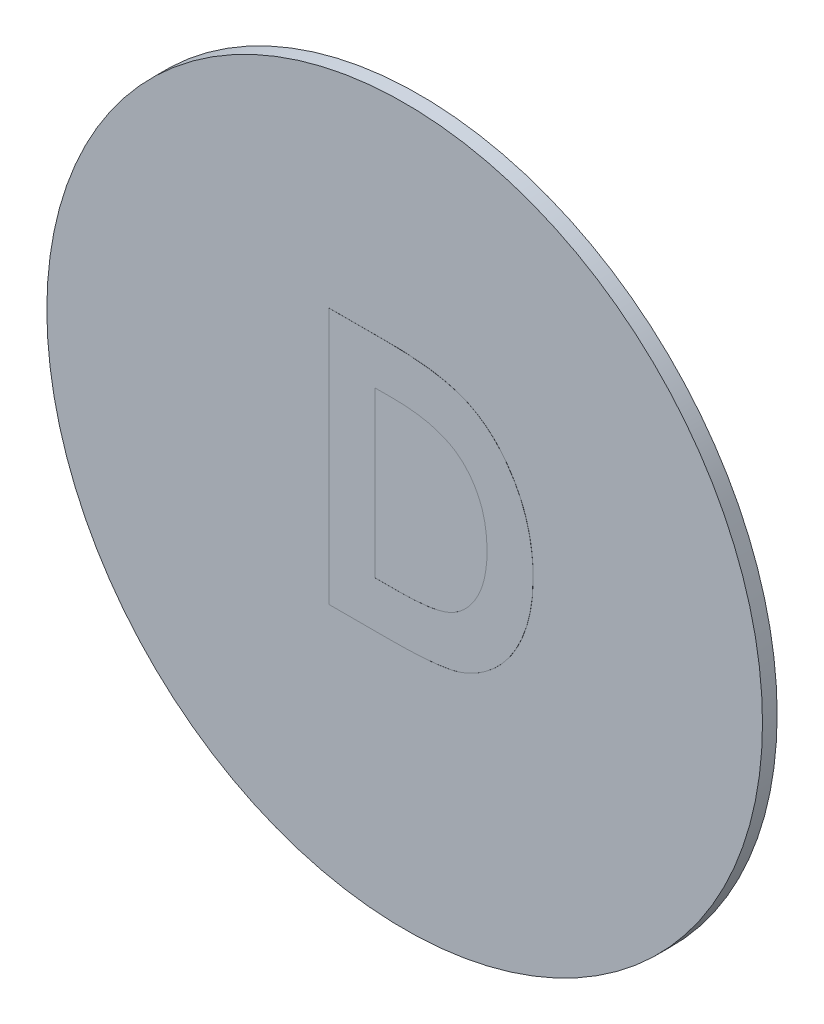
SolidWorks part; units mm, degrees
ref_plane "Front Plane" through (0, 0, 0) normal (0, 0, 1) x (1, 0, 0)
ref_plane "Top Plane" through (0, 0, 0) normal (0, 1, 0) x (1, 0, 0)
ref_plane "Right Plane" through (0, 0, 0) normal (1, 0, 0) x (0, 0, -1)
sketch "Sketch1" plane through (0, 0, 0) normal (0, 0, 1) x (1, 0, 0)
  circle A0 centre (-23.6094, 8.0067) radius 4.88
extrude "Boss-Extrude1" add sketch "Sketch1" along normal blind 0.2
sketch "Sketch2" plane through (0, 0, 0.2) normal (0, 0, 1) x (1, 0, 0)
  text T0 "<b>D</b>"
  point P1 (-25.2325, 5.3673)
  point P2 (-24.5065, 7.4395)
  point P3 (-25.0221, 6.8208)
extrude "Boss-Extrude2" add sketch "Sketch2" along normal blind 0.001
